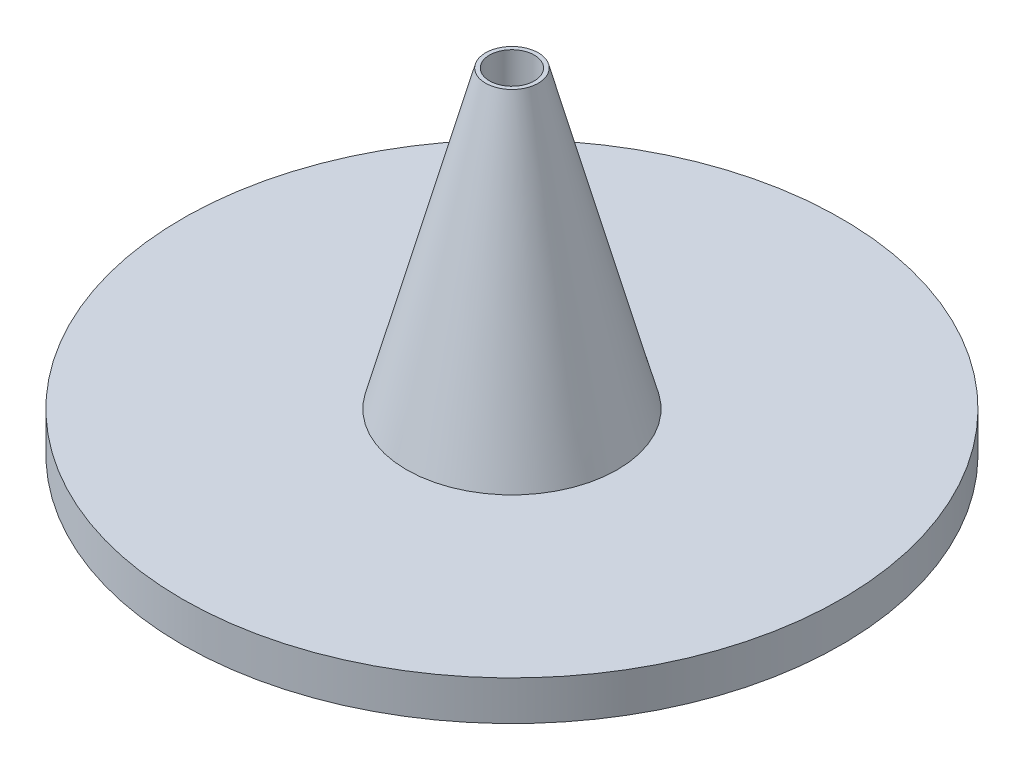
SolidWorks part; units mm, degrees
ref_plane "Front Plane" through (0, 0, 0) normal (0, 0, 1) x (1, 0, 0)
ref_plane "Top Plane" through (0, 0, 0) normal (0, 1, 0) x (1, 0, 0)
ref_plane "Right Plane" through (0, 0, 0) normal (1, 0, 0) x (0, 0, -1)
sketch "Sketch1" plane through (0, 0, 0) normal (0, 1, 0) x (1, 0, 0)
  circle A0 centre (0, 0) radius 25
  dimension "D1" = 50
extrude "Boss-Extrude1" add sketch "Sketch1" along normal blind 3
sketch "Sketch2" plane through (0, 0, 0) normal (1, 0, 0) x (0, 0, -1)
  line L0 (0, 0) -> (0, 25.3923) construction
  line L1 (-8, 3) -> (-2, 25.3923)
  line L2 (25, 3) -> (-25, 3) construction
  line L3 (0, 25.3923) -> (0, 3)
  line L4 (0, 3) -> (-8, 3)
  line L5 (0, 25.3923) -> (-2, 25.3923)
  line L6 (-8, 3) -> (-8, 12.0762) construction
  point P4 (0, 17.8745)
  dimension "D2" = 8
  dimension "D3" = 2
  dimension "D4" = 15
revolve "Revolve1" add sketch "Sketch2" angle 360 about L0
sketch "Sketch3" plane through (0, 25.3923, 0) normal (0, 1, 0) x (1, 0, 0)
  circle A0 centre (0, 0) radius 1.7
  dimension "D1" = 3.4
extrude "Cut-Extrude1" cut sketch "Sketch3" against normal through all
